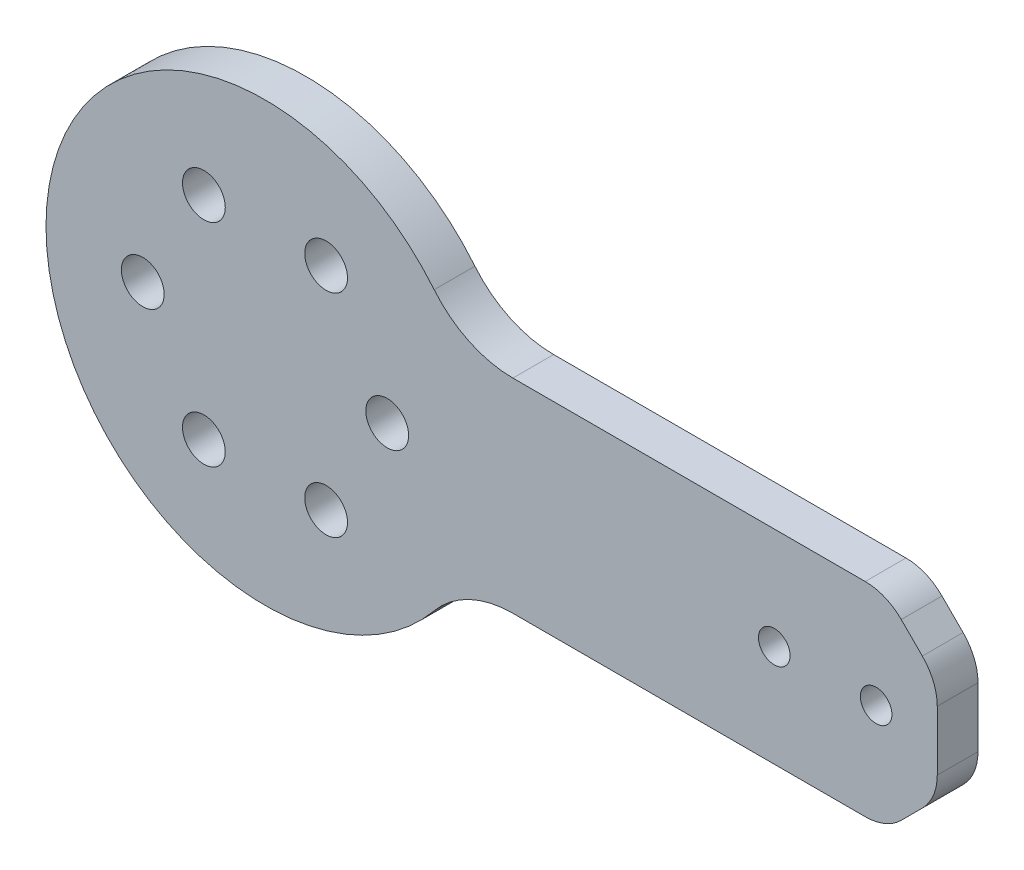
SolidWorks part; units mm, degrees
material "Thornel Mat VMA"
ref_plane "前视基准面" through (0, 0, 0) normal (0, 0, 1) x (1, 0, 0)
ref_plane "上视基准面" through (0, 0, 0) normal (0, 1, 0) x (1, 0, 0)
ref_plane "右视基准面" through (0, 0, 0) normal (1, 0, 0) x (0, 0, -1)
other "Configuration Table"
sketch "草图1" plane through (0, 0, 0) normal (0, 0, 1) x (1, 0, 0)
  line L0 (0, 0) -> (66, 0) construction
  line L1 (19.0329, 10) -> (66, 10)
  line L2 (66, -10) -> (66, 10)
  line L4 (66, -10) -> (19.0329, -10)
  circle A0 centre (0, 0) radius 21.5 construction
  circle A1 centre (12, 0) radius 2.1
  circle A2 centre (6, -10.3923) radius 2.1
  circle A3 centre (-6, -10.3923) radius 2.1
  circle A4 centre (-12, 0) radius 2.1
  circle A5 centre (-6, 10.3923) radius 2.1
  circle A6 centre (6, 10.3923) radius 2.1
  arc A7 (19.0329, 10) -> (19.0329, -10) centre (0, 0) ccw
  dimension "D2" = 43
  dimension "D4" = 4.2
  dimension "D7" = 10
  dimension "D1" = 66
  dimension "D3" = 12
  dimension "D6" = 10
  dimension "D5" = 6
extrude "凸台-拉伸1" add sketch "草图1" along normal blind 4
chamfer "倒角1" distance 5 angle 45 2 edges at (66, -10, 2) (66, 10, 2)
sketch "草图2" plane through (0, 0, 4) normal (0, 0, 1) x (1, 0, 0)
  line L0 (66, 0) -> (0, 0) construction
  line L1 (66, -5) -> (66, 5) construction
  circle A0 centre (60, 0) radius 1.55
  circle A1 centre (50, 0) radius 1.55
  dimension "D3" = 3.1
  dimension "D4" = 3.1
  dimension "D1" = 6
  dimension "D2" = 10
extrude "切除-拉伸1" cut sketch "草图2" against normal through all
fillet "圆角1" radius 10 2 edges at (19.0329, -10, 2) (19.0329, 10, 2)
fillet "圆角2" radius 5 4 edges at (61, -10, 2) (66, -5, 2) (66, 5, 2) (61, 10, 2)
